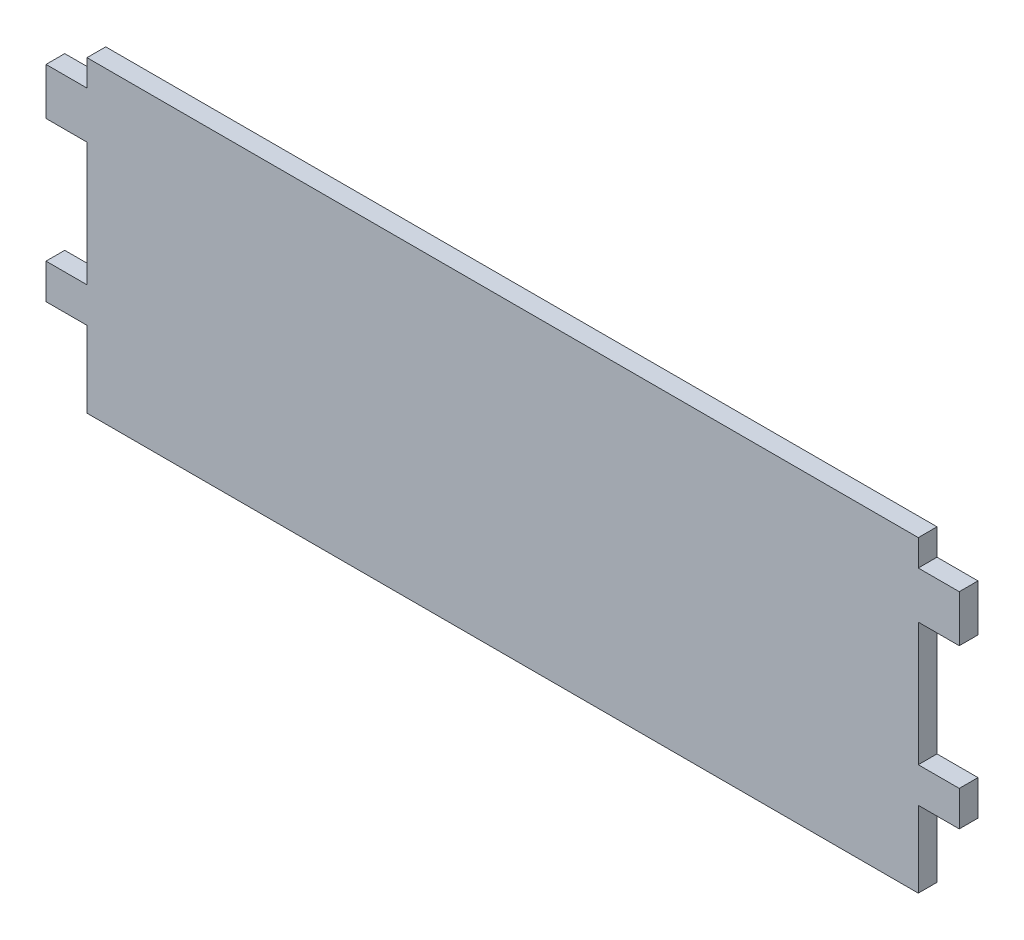
SolidWorks part; units mm, degrees
ref_plane "前视基准面" through (0, 0, 0) normal (0, 0, 1) x (1, 0, 0)
ref_plane "上视基准面" through (0, 0, 0) normal (0, 1, 0) x (1, 0, 0)
ref_plane "右视基准面" through (0, 0, 0) normal (1, 0, 0) x (0, 0, -1)
sketch "草图1" plane through (0, 0, 0) normal (0, 0, 1) x (1, 0, 0)
  line L0 (0, 0) -> (0, 38.8053) construction
  line L11 (0, 0) -> (-51.2518, 0) construction
  line L12 (39, 4) -> (-39, 4)
  line L13 (-39, 4) -> (-39, 0)
  line L14 (-39, 0) -> (-35.5, 0)
  line L15 (-35.5, 0) -> (-35.5, -13.55) construction
  line L16 (-35.5, -13.55) -> (35.5, -13.55)
  line L17 (35.5, 0) -> (35.5, -13.55) construction
  line L18 (39, 0) -> (35.5, 0)
  line L19 (39, 4) -> (39, 0)
  line L20 (-35.5, -10.55) -> (-39, -10.55)
  line L21 (-39, -10.55) -> (-39, -13.55)
  line L22 (-39, -13.55) -> (-35.5, -13.55)
  line L23 (-35.5, 0) -> (-35.5, -10.55)
  line L24 (39, -13.55) -> (35.5, -13.55)
  line L25 (39, -10.55) -> (39, -13.55)
  line L26 (35.5, -10.55) -> (39, -10.55)
  line L27 (35.5, 0) -> (35.5, -10.55)
  line L28 (-39, 2) -> (-43.2943, 2) construction
  point P6 (-37.25, 0)
  point P12 (0, -13.55)
  point P15 (0, 4)
  dimension "D1" = 3.5
  dimension "D2" = 4
  dimension "D3" = 71
  dimension "D4" = 12.55
  dimension "D5" = 3
extrude "主体" add sketch "草图1" along normal blind 1.6
ref_plane "旋转轴所在面" through (0, 0, 0.8) normal (0, 0, -1) x (-1, 0, 0)
sketch "旋转轴示意" plane through (0, 0, 0.8) normal (0, 0, -1) x (-1, 0, 0)
  line L0 (-39, 2) -> (-50.9061, 2) construction
  line L1 (-39, 0) -> (-39, 4) construction
sketch "草图3" plane through (0, 0, 0) normal (0, 0, -1) x (-1, 0, 0)
  line L0 (-35.5, 4) -> (-35.5, 6.25)
  line L1 (-39, 4) -> (39, 4) construction
  line L2 (-35.5, 6.25) -> (35.5, 6.25)
  line L3 (35.5, 6.25) -> (35.5, 4)
  line L4 (35.5, 4) -> (-35.5, 4)
  line L5 (-35.5, -10.55) -> (-35.5, 0) construction
  line L6 (35.5, 0) -> (35.5, -10.55) construction
  line L7 (-35.5, -20.05) -> (-35.5, -13.55)
  line L8 (-35.5, -13.55) -> (35.5, -13.55)
  line L9 (35.5, -13.55) -> (35.5, -20.05)
  line L10 (35.5, -20.05) -> (-35.5, -20.05)
  line L11 (39, -13.55) -> (-39, -13.55) construction
  dimension "D1" = 2.25
  dimension "D2" = 6.5
extrude "结构补强" add sketch "草图3" against normal up to surface (1.6 mm away) up to face at (0, -5.1083, 1.6)
sketch "草图4" plane through (0, 0, 0) normal (0, 0, -1) x (-1, 0, 0)
  line L0 (-39, -12.05) -> (39, -12.05) construction
  line L1 (-39, -13.55) -> (-39, -10.55) construction
  line L2 (39, -10.55) -> (39, -13.55) construction
  text T0 "  厦门大学" font "钟齐志莽行书" height 12.5
extrude "Logo-看看能不能刻字" cut sketch "草图4" along normal through all and the other way blind 1
